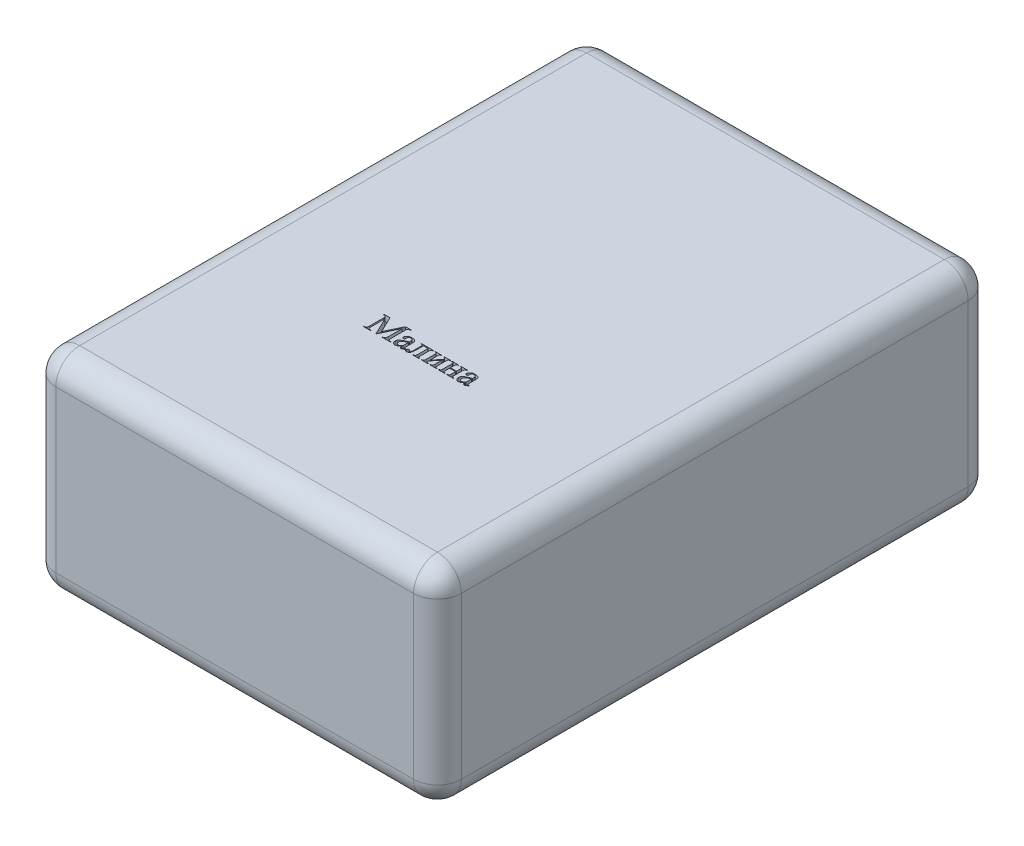
SolidWorks part; units mm, degrees
material "PF"
ref_plane "Спереди" through (0, 0, 0) normal (0, 0, 1) x (1, 0, 0)
ref_plane "Сверху" through (0, 0, 0) normal (0, 1, 0) x (1, 0, 0)
ref_plane "Справа" through (0, 0, 0) normal (1, 0, 0) x (0, 0, -1)
sketch "Эскиз1" plane through (0, 0, 0) normal (0, 1, 0) x (1, 0, 0)
  line L1 (-34, -46.5) -> (34, -46.5)
  line L2 (-34, -46.5) -> (-34, 46.5)
  line L3 (-34, 46.5) -> (34, 46.5)
  line L4 (34, -46.5) -> (34, 46.5)
  line L5 (-34, -46.5) -> (34, 46.5) construction
  line L6 (-34, 46.5) -> (34, -46.5) construction
  point P0 (0, 0)
  dimension "D1" = 93
  dimension "D2" = 68
extrude "Бобышка-Вытянуть1" add sketch "Эскиз1" along normal blind 35
sketch "Эскиз2" plane through (0, 0, 0) normal (0, -1, 0) x (1, 0, 0)
  line L0 (34, 0) -> (-34, 0) construction
  line L1 (34, 46.5) -> (34, -46.5) construction
  line L2 (-34, -46.5) -> (-34, 46.5) construction
  line L3 (0, 0) -> (-20, 0) construction
  line L4 (0, 0) -> (20, 0) construction
  circle A0 centre (20, 0) radius 1.5
  circle A1 centre (-20, 0) radius 1.5
  dimension "D1" = 3
  dimension "D2" = 3
  dimension "D3" = 40
  dimension "D4" = 20
extrude "Вырез-Вытянуть1" cut sketch "Эскиз2" against normal blind 5
sketch "Эскиз3" plane through (0, 35, 0) normal (0, 1, 0) x (1, 0, 0)
  text T0 "Малина"
extrude "Вырез-Вытянуть2" cut sketch "Эскиз3" against normal blind 1
fillet "Скругление1" radius 4 12 edges at (-34, 17.5, 46.5) (34, 17.5, 46.5) (0, 0, 46.5) (-34, 0, 0) (0, 35, 46.5) (-34, 35, 0) (34, 35, 0) (34, 0, 0) (0, 35, -46.5) (-34, 17.5, -46.5) (0, 0, -46.5) (34, 17.5, -46.5)
